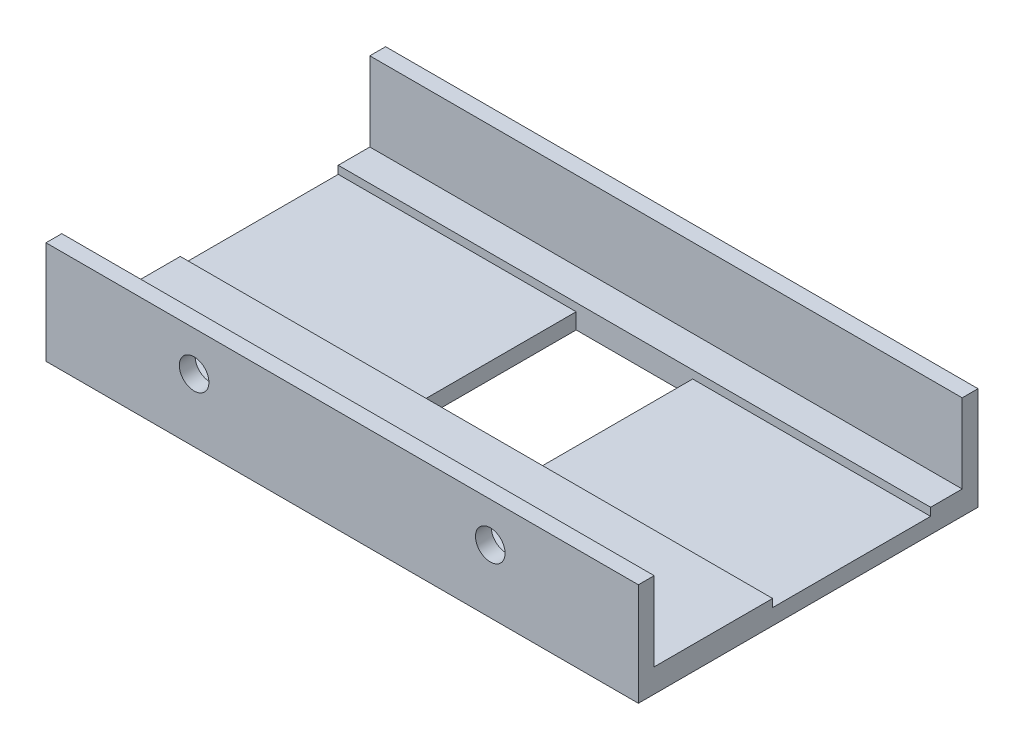
SolidWorks part; units mm, degrees
material "1345 Alloy"
ref_plane "Front Plane" through (0, 0, 0) normal (0, 0, 1) x (1, 0, 0)
ref_plane "Top Plane" through (0, 0, 0) normal (0, 1, 0) x (1, 0, 0)
ref_plane "Right Plane" through (0, 0, 0) normal (1, 0, 0) x (0, 0, -1)
sketch "Sketch1" plane through (0, 0, 0) normal (0, 1, 0) x (1, 0, 0)
  line L1 (-37.5, 21.5) -> (37.5, 21.5)
  line L2 (-37.5, 21.5) -> (-37.5, -21.5)
  line L3 (-37.5, -21.5) -> (37.5, -21.5)
  line L4 (37.5, 21.5) -> (37.5, -21.5)
  line L5 (-37.5, 21.5) -> (37.5, -21.5) construction
  line L6 (-37.5, -21.5) -> (37.5, 21.5) construction
  point P0 (0, 0)
  dimension "D1" = 43
  dimension "D2" = 75
extrude "Boss-Extrude1" add sketch "Sketch1" along normal blind 3
sketch "Sketch2" plane through (0, 3, 0) normal (0, 1, 0) x (1, 0, 0)
  line L0 (37.5, -21.5) -> (37.5, 21.5) construction
  line L1 (-37.5, 21.5) -> (37.5, 21.5)
  line L2 (-37.5, 21.5) -> (-37.5, 19.5)
  line L3 (-37.5, 19.5) -> (37.5, 19.5)
  line L4 (37.5, 21.5) -> (37.5, 19.5)
  dimension "D1" = 2
extrude "Boss-Extrude2" add sketch "Sketch2" along normal blind 10
sketch "Sketch3" plane through (0, 3, 0) normal (0, 1, 0) x (1, 0, 0)
  line L0 (37.5, -21.5) -> (37.5, 19.5) construction
  line L1 (-37.5, -21.5) -> (37.5, -21.5)
  line L2 (-37.5, -21.5) -> (-37.5, -19.5)
  line L3 (-37.5, -19.5) -> (37.5, -19.5)
  line L4 (37.5, -21.5) -> (37.5, -19.5)
  dimension "D1" = 2
extrude "Boss-Extrude3" add sketch "Sketch3" along normal up to surface (10 mm away) up to face at (0, 13, -20.5)
sketch "Sketch4" plane through (0, 0, 21.5) normal (0, 0, 1) x (1, 0, 0)
  line L4 (0, 0) -> (0, 13) construction
  line L5 (-37.5, 0) -> (37.5, 0) construction
  line L6 (-37.5, 13) -> (37.5, 13) construction
  line L8 (-39.5, -2) -> (39.5, -2)
  line L9 (39.5, -2) -> (39.5, 15)
  line L10 (39.5, 15) -> (-39.5, 15)
  line L11 (-39.5, 15) -> (-39.5, -2)
  line L12 (-39.5, -2) -> (39.5, -2)
  line L13 (39.5, -2) -> (39.5, 15)
  line L14 (39.5, 15) -> (-39.5, 15)
  line L15 (-39.5, 15) -> (-39.5, -2)
  circle A1 centre (18.75, 8) radius 1.875
  circle A2 centre (-18.75, 8) radius 1.875
  circle A3 centre (-18.75, 8) radius 1.875
  dimension "D1" = 2
  dimension "D2" = 0.5
extrude "Cut-Extrude2" cut sketch "Sketch4" against normal up to surface (2 mm away) flip side to cut up to face at (0, 8, 19.5)
sketch "Sketch6" plane through (0, 3, 0) normal (0, 1, 0) x (1, 0, 0)
  line L0 (-37.5, 19.5) -> (-37.5, -8.5) construction
  line L1 (-37.5, 19.5) -> (-37.5, -19.5) construction
  line L2 (-37.5, -8.5) -> (37.5, -8.5) construction
  line L3 (37.5, -19.5) -> (37.5, 19.5) construction
  line L4 (37.5, -8.5) -> (37.5, 19.5) construction
  line L5 (37.5, 19.5) -> (-37.5, 19.5) construction
  line L6 (-22.9033, -8.5) -> (22.0967, -8.5) construction
  line L7 (-37.5, 5.5) -> (37.5, 5.5) construction
  line L8 (0, 19.5) -> (0, -8.5) construction
  line L10 (-7.375, 15.5) -> (7.375, 15.5)
  line L11 (-7.375, 15.5) -> (-7.375, -4.5)
  line L12 (-7.375, -4.5) -> (7.375, -4.5)
  line L13 (7.375, 15.5) -> (7.375, -4.5)
  line L14 (-7.375, 15.5) -> (7.375, -4.5) construction
  line L15 (-7.375, -4.5) -> (7.375, 15.5) construction
  point P17 (0, 5.5)
  dimension "D1" = 14.75
  dimension "D2" = 20
  dimension "D3" = 4
extrude "Cut-Extrude3" cut sketch "Sketch6" against normal through all
sketch "Sketch7" plane through (0, 3, 0) normal (0, 1, 0) x (1, 0, 0)
  line L0 (-37.5, 19.5) -> (-37.5, -19.5) construction
  line L1 (-37.5, 15.5) -> (37.5, 15.5)
  line L2 (-37.5, 15.5) -> (-37.5, -4.5)
  line L3 (-37.5, -4.5) -> (37.5, -4.5)
  line L4 (37.5, 15.5) -> (37.5, -4.5)
  line L5 (37.5, -19.5) -> (37.5, 19.5) construction
  line L6 (7.375, 15.5) -> (-7.375, 15.5) construction
  line L7 (-7.375, -4.5) -> (7.375, -4.5) construction
extrude "Cut-Extrude4" cut sketch "Sketch7" against normal blind 1
